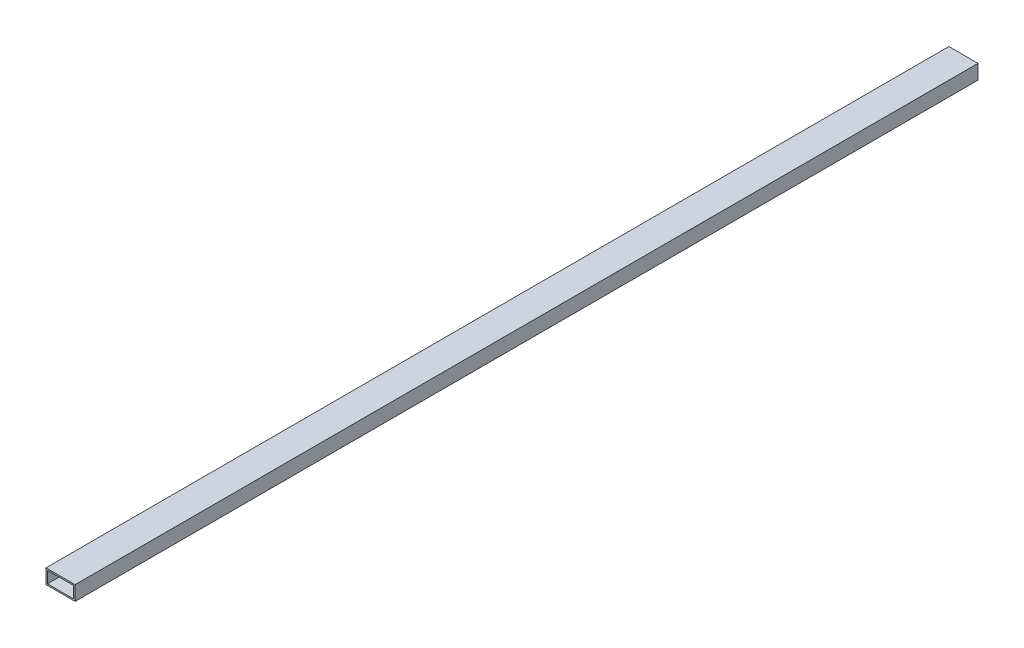
SolidWorks part; units mm, degrees
ref_plane "前视基准面" through (0, 0, 0) normal (0, 0, 1) x (1, 0, 0)
ref_plane "上视基准面" through (0, 0, 0) normal (0, 1, 0) x (1, 0, 0)
ref_plane "右视基准面" through (0, 0, 0) normal (1, 0, 0) x (0, 0, -1)
sketch "草图1" plane through (0, 0, 0) normal (0, 0, 1) x (1, 0, 0)
  line L1 (10, -5) -> (-10, -5)
  line L2 (10, -5) -> (10, 5)
  line L3 (10, 5) -> (-10, 5)
  line L4 (-10, -5) -> (-10, 5)
  line L7 (9, -4) -> (-9, -4)
  line L8 (9, -4) -> (9, 4)
  line L9 (9, 4) -> (-9, 4)
  line L10 (-9, -4) -> (-9, 4)
  point P0 (0, 0)
  point P6 (0, 0)
  dimension "D1" = 20
  dimension "D2" = 10
  dimension "D3" = 18
  dimension "D4" = 8
  dimension "D5" = 1
  dimension "D6" = 1
extrude "凸台-拉伸1" add sketch "草图1" along normal blind 620
